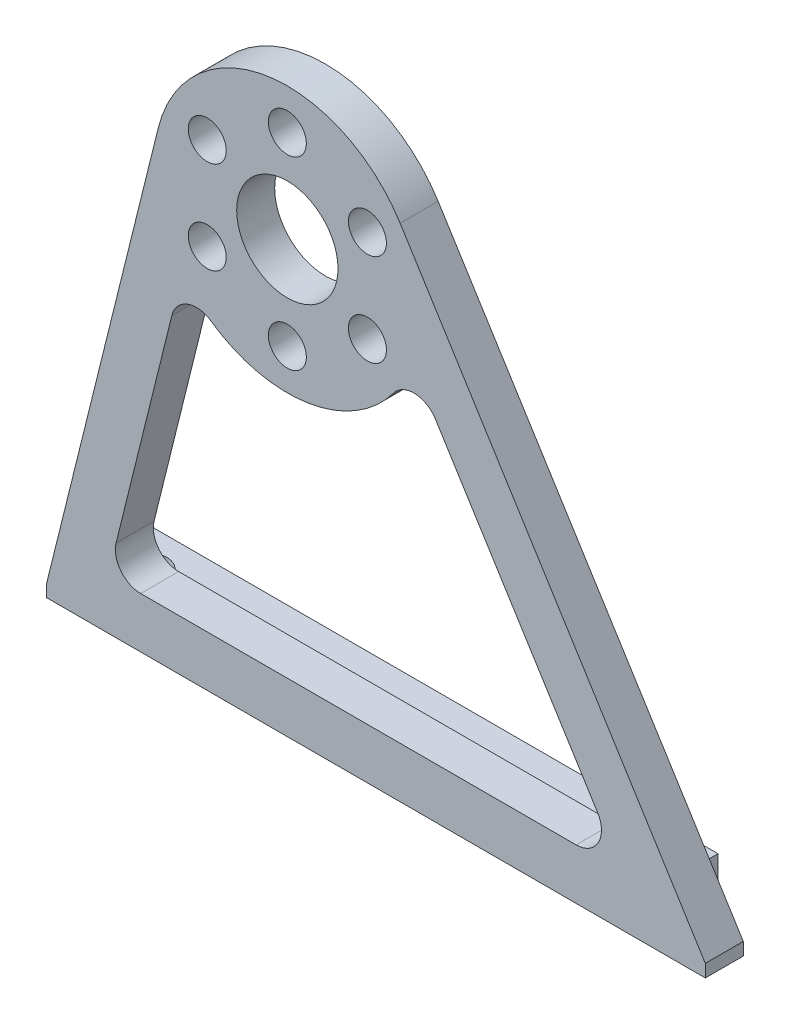
SolidWorks part; units mm, degrees
ref_plane "前视基准面" through (0, 0, 0) normal (0, 0, 1) x (1, 0, 0)
ref_plane "上视基准面" through (0, 0, 0) normal (0, 1, 0) x (1, 0, 0)
ref_plane "右视基准面" through (0, 0, 0) normal (1, 0, 0) x (0, 0, -1)
sketch "草图1" plane through (0, 0, 0) normal (0, 0, 1) x (1, 0, 0)
  line L0 (-10.1914, 2.5269) -> (-19, -33)
  line L1 (-9.1155, -9.7549) -> (-13.5198, -27.5187)
  line L2 (33, -33) -> (8.9047, 5.5638)
  line L3 (-19, -33) -> (-19, -34)
  line L4 (-19, -34) -> (33, -34)
  line L5 (33, -34) -> (33, -33)
  line L6 (-11.5786, -30) -> (22.801, -30)
  line L7 (24.4972, -26.9402) -> (11.6919, -6.4458)
  arc A0 (8.9047, 5.5638) -> (-10.1914, 2.5269) centre (0, 0) ccw
  arc A1 (8.3965, -6.3047) -> (11.6919, -6.4458) centre (9.9958, -7.5056) cw
  arc A2 (22.801, -30) -> (24.4972, -26.9402) centre (22.801, -28) ccw
  arc A3 (-11.5786, -30) -> (-13.5198, -27.5187) centre (-11.5786, -28) cw
  arc A4 (-6.0264, -8.5984) -> (-9.1155, -9.7549) centre (-7.1742, -10.2362) ccw
  circle A6 centre (0, 0) radius 4
  arc A7 (-6.0264, -8.5984) -> (8.3965, -6.3047) centre (0, 0) ccw
  circle A9 centre (0, 7.3) radius 1.5
  circle A10 centre (6.322, 3.65) radius 1.5
  circle A11 centre (6.322, -3.65) radius 1.5
  circle A12 centre (0, -7.3) radius 1.5
  circle A13 centre (-6.322, -3.65) radius 1.5
  circle A14 centre (-6.322, 3.65) radius 1.5
  point P37 (0, 0)
  dimension "D2" = 21
  dimension "D9" = 2
  dimension "D10" = 2
  dimension "D13" = 8
  dimension "D14" = 2
  dimension "D16" = 3
  dimension "D3" = 4
  dimension "D4" = 19
  dimension "D5" = 52
  dimension "D6" = 1
  dimension "D7" = 4
  dimension "D8" = 4
  dimension "D11" = 34
  dimension "D12" = 1
  dimension "D17" = 6
extrude "凸台-拉伸1" add sketch "草图1" along normal blind 6
sketch "草图4" plane through (0, -34, 0) normal (0, -1, 0) x (-1, 0, 0)
  line L0 (19, -3) -> (-33, -3) construction
  line L1 (19, -6) -> (19, 0) construction
  line L2 (-33, -6) -> (-33, 0) construction
  circle A0 centre (14, -3) radius 1.5
  circle A1 centre (-23, -3) radius 1.5
  dimension "D1" = 3
  dimension "D2" = 3
  dimension "D3" = 37
  dimension "D4" = 5
extrude "切除-拉伸2" cut sketch "草图4" against normal blind 3
sketch "草图5" plane through (0, 0, 0) normal (0, 0, -1) x (-1, 0, 0)
  line L0 (22.8482, -31) -> (-28, -31)
  line L1 (-28, -31) -> (-28, -36.1984)
  line L2 (-28, -36.1984) -> (-37.7359, -36.1984)
  line L3 (-37.7359, -36.1984) -> (-37.7359, 13.6767)
  line L4 (-37.7359, 13.6767) -> (23.3606, 13.6767)
  line L5 (23.3606, 13.6767) -> (23.3606, -30.9888)
  line L6 (23.3606, -30.9888) -> (22.8482, -31)
  line L7 (19, -34) -> (-33, -34) construction
  line L8 (19, -33) -> (19, -34) construction
  dimension "D1" = 3
  dimension "D2" = 47
extrude "切除-拉伸3" cut sketch "草图5" against normal blind 3
